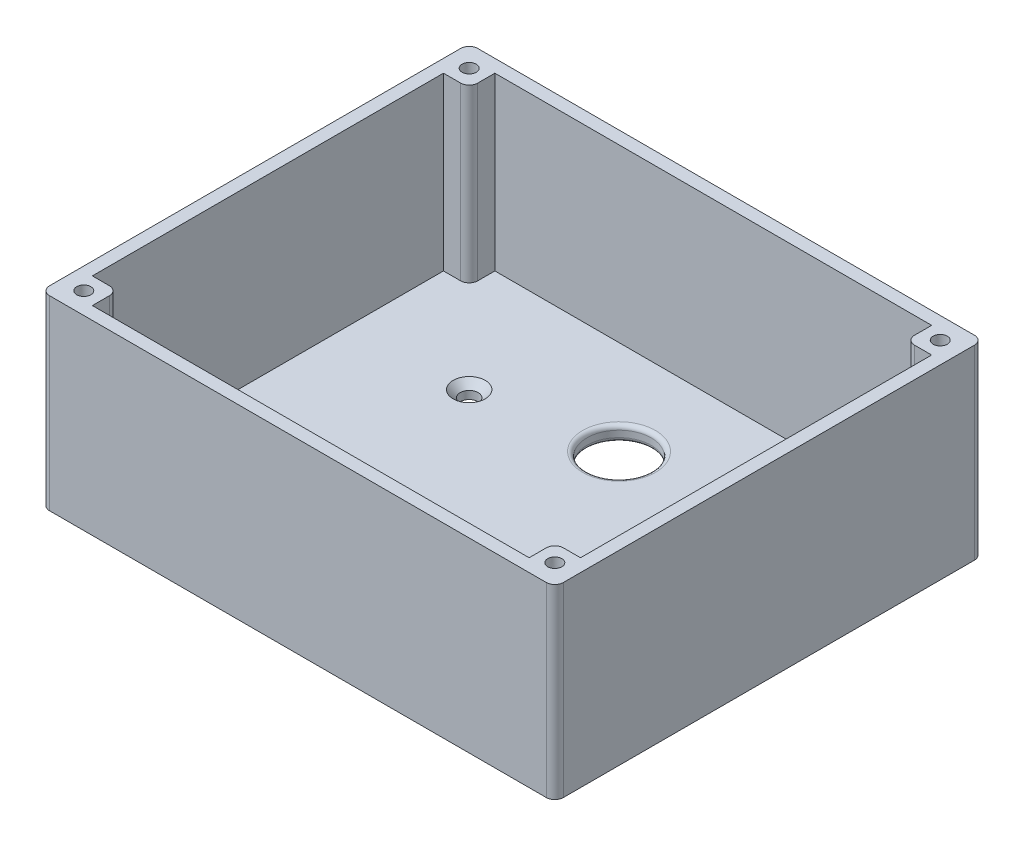
SolidWorks part; units mm, degrees
ref_plane "Front Plane" through (0, 0, 0) normal (0, 0, 1) x (1, 0, 0)
ref_plane "Top Plane" through (0, 0, 0) normal (0, 1, 0) x (1, 0, 0)
ref_plane "Right Plane" through (0, 0, 0) normal (1, 0, 0) x (0, 0, -1)
sketch "Sketch1" plane through (0, 0, 0) normal (0, 1, 0) x (1, 0, 0)
  line L1 (60, -50) -> (-60, -50)
  line L2 (60, -50) -> (60, 50)
  line L3 (60, 50) -> (-60, 50)
  line L4 (-60, -50) -> (-60, 50)
  line L5 (60, -50) -> (-60, 50) construction
  line L6 (60, 50) -> (-60, -50) construction
  point P0 (0, 0)
  dimension "D1" = 100
  dimension "D2" = 120
extrude "Bottom" add sketch "Sketch1" along normal blind 3.5
sketch "Sketch3" plane through (0, 3.5, 0) normal (0, 1, 0) x (1, 0, 0)
  line L0 (-60, 50) -> (60, 50)
  line L1 (60, 50) -> (60, -50)
  line L2 (60, -50) -> (-60, -50)
  line L3 (-60, -50) -> (-60, 50)
  line L4 (-51, 47) -> (51, 47)
  line L5 (57, 41) -> (57, -41)
  line L6 (51, -47) -> (-51, -47)
  line L8 (-57, 41) -> (-51, 41)
  line L9 (-51, 41) -> (-51, 47)
  line L10 (51, 47) -> (51, 41)
  line L11 (51, 41) -> (57, 41)
  line L12 (57, -41) -> (51, -41)
  line L13 (51, -41) -> (51, -47)
  line L14 (-57, -41) -> (-51, -41)
  line L15 (-51, -41) -> (-51, -47)
  line L16 (-57, -41) -> (-57, 41)
  dimension "D1" = 3
  dimension "D2" = 3
  dimension "D3" = 3
  dimension "D4" = 3
  dimension "D5" = 6
extrude "Wall" add sketch "Sketch3" along normal blind 40
sketch "Sketch4" plane through (0, 43.5, 0) normal (0, 1, 0) x (1, 0, 0)
  line L0 (-60, 50) -> (-60, -50) construction
  line L1 (60, 50) -> (-60, 50) construction
  line L2 (60, -50) -> (60, 50) construction
  line L3 (-60, -50) -> (60, -50) construction
  circle A0 centre (-55, 45) radius 1.65
  circle A1 centre (55, 45) radius 1.65
  circle A2 centre (55, -45) radius 1.65
  circle A3 centre (-55, -45) radius 1.65
  dimension "D1" = 3.3
  dimension "D4" = 5
  dimension "D2" = 5
  dimension "D3" = 5
  dimension "D5" = 5
extrude "Top Plate Screw Holes" cut sketch "Sketch4" against normal blind 30 draft 1
fillet "Fillet1" radius 2 1 edges at (-51, 23.5, 41)
fillet "Fillet2" radius 2 1 edges at (51, 23.5, 41)
fillet "Fillet3" radius 2 1 edges at (51, 23.5, -41)
fillet "Fillet4" radius 2 1 edges at (-51, 23.5, -41)
fillet "Fillet5" radius 2 1 edges at (-60, 21.75, -50)
fillet "Fillet6" radius 2 1 edges at (60, 21.75, -50)
fillet "Fillet7" radius 2 1 edges at (60, 21.75, 50)
fillet "Fillet8" radius 2 1 edges at (-60, 21.75, 50)
sketch "M4 Mount" plane through (0, 3.5, 0) normal (0, -1, 0) x (1, 0, 0)
  line L0 (60, 48) -> (60, -48) construction
  line L1 (0, 0) -> (23.8675, 0) construction
  line L2 (0, 0) -> (0, -19.9393) construction
  circle A0 centre (30, -20) radius 2.1
  circle A1 centre (30, 20) radius 2.1
  circle A2 centre (-30, 20) radius 2.1
  circle A3 centre (-30, -20) radius 2.1
  dimension "D1" = 4.2
  dimension "D2" = 30
  dimension "D3" = 20
  dimension "D4" = 20
extrude "M4 Mount Cut" cut sketch "M4 Mount" along normal through all
sketch "M4 Screw Heads" plane through (0, 3.5, 0) normal (0, 1, 0) x (1, 0, 0)
  circle A0 centre (30, -20) radius 3.75
  circle A1 centre (30, 20) radius 3.75
  circle A2 centre (-30, 20) radius 3.75
  circle A3 centre (-30, -20) radius 3.75
  dimension "D1" = 7.5
extrude "Cut-Extrude3" cut sketch "M4 Screw Heads" against normal blind 10 draft 45
sketch "Sketch7" plane through (0, 0, 0) normal (0, -1, 0) x (1, 0, 0)
  line L0 (58, -50) -> (-58, -50) construction
  line L1 (60, 48) -> (60, -48) construction
  circle A0 centre (0, -25) radius 7.5
  point P2 (0, -50)
  dimension "D1" = 15
  dimension "D2" = 25
  dimension "D3" = 60
extrude "USB Cabel Cut" cut sketch "Sketch7" against normal through all
fillet "Fillet9" radius 1 1 edges at (0, 0, -32.5)
fillet "Fillet10" radius 1 1 edges at (0, 3.5, -17.5)
equation "\"BOXWALL\"=3"
equation "\"D1@Sketch3\"=\"BOXWALL\""
equation "\"D2@Sketch3\"=\"BOXWALL\""
equation "\"D3@Sketch3\"=\"BOXWALL\""
equation "\"D4@Sketch3\"=\"BOXWALL\""
